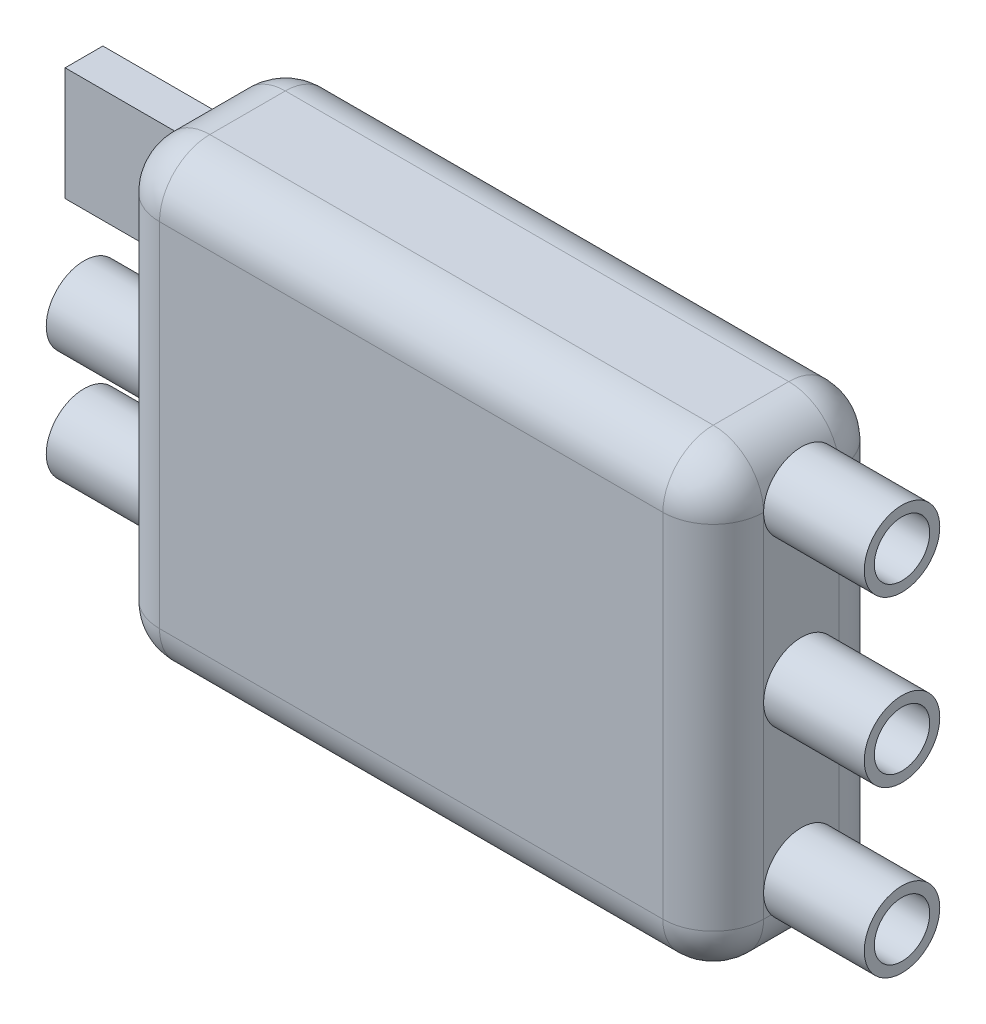
SolidWorks part; units mm, degrees
ref_plane "Front Plane" through (0, 0, 0) normal (0, 0, 1) x (1, 0, 0)
ref_plane "Top Plane" through (0, 0, 0) normal (0, 1, 0) x (1, 0, 0)
ref_plane "Right Plane" through (0, 0, 0) normal (1, 0, 0) x (0, 0, -1)
sketch "Sketch1" plane through (0, 0, 0) normal (0, 0, 1) x (1, 0, 0)
  line L1 (10, -9) -> (-10, -9)
  line L2 (12, -7) -> (12, 7)
  line L3 (10, 9) -> (-10, 9)
  line L4 (-12, -7) -> (-12, 7)
  line L5 (12, -9) -> (-12, 9) construction
  line L6 (12, 9) -> (-12, -9) construction
  arc A0 (-10, -9) -> (-12, -7) centre (-10, -7) cw
  arc A1 (10, -9) -> (12, -7) centre (10, -7) ccw
  arc A2 (12, 7) -> (10, 9) centre (10, 7) ccw
  arc A3 (-10, 9) -> (-12, 7) centre (-10, 7) ccw
  point P0 (0, 0)
  dimension "D2" = 2
  dimension "D1" = 18
  dimension "24" = 24
extrude "Boss-Extrude1" add sketch "Sketch1" along normal blind 7
fillet "Fillet1" radius 2 16 edges at (11.4142, -8.4142, 0) (0, -9, 0) (-11.4142, -8.4142, 0) (-12, 0, 0) (-11.4142, 8.4142, 0) (0, 9, 0) (11.4142, 8.4142, 0) (11.4142, 8.4142, 7) (12, 0, 7) (11.4142, -8.4142, 7) (0, -9, 7) (-11.4142, -8.4142, 7) (-12, 0, 7) (-11.4142, 8.4142, 7) (12, 0, 0) (0, 9, 7)
sketch "Sketch3" plane through (12, 0, 0) normal (1, 0, 0) x (0, 0, -1)
  line L0 (-3.5, 7) -> (-3.5, -6.0977) construction
  line L1 (-5, 7) -> (-2, 7) construction
  line L4 (-2, -7) -> (-2, 7) construction
  circle A0 centre (-3.5, -6.0977) radius 1.1
  circle A2 centre (-3.5, 0.4512) radius 1.1
  circle A4 centre (-3.5, 7) radius 1.1
  circle A5 centre (-3.5, 7) radius 1.5
  circle A6 centre (-3.5, 0.4512) radius 1.5
  circle A7 centre (-3.5, -6.0977) radius 1.5
  dimension "D1" = 0.4
extrude "Boss-Extrude2" add sketch "Sketch3" along normal blind 4
sketch "Sketch4" plane through (-12, 0, 0) normal (-1, 0, 0) x (0, 0, 1)
  line L0 (3.5, 7) -> (3.5, -5.8843) construction
  line L1 (5, 7) -> (2, 7) construction
  line L3 (2.75, 7.6708) -> (4.25, 7.6708)
  line L4 (2.75, 7.6708) -> (2.75, 3.1708)
  line L5 (2.75, 3.1708) -> (4.25, 3.1708)
  line L6 (4.25, 7.6708) -> (4.25, 3.1708)
  circle A0 centre (3.5, -0.844) radius 0.6403
  circle A1 centre (3.5, -0.844) radius 1.5
  circle A2 centre (3.5, -5.244) radius 1.1
  circle A3 centre (3.5, -5.244) radius 1.5
  dimension "D3" = 3
  dimension "D4" = 0.4
  dimension "D1" = 4.5
  dimension "D2" = 1.5
  dimension "D5" = 4.4
extrude "Boss-Extrude3" add sketch "Sketch4" along normal blind 4.5
